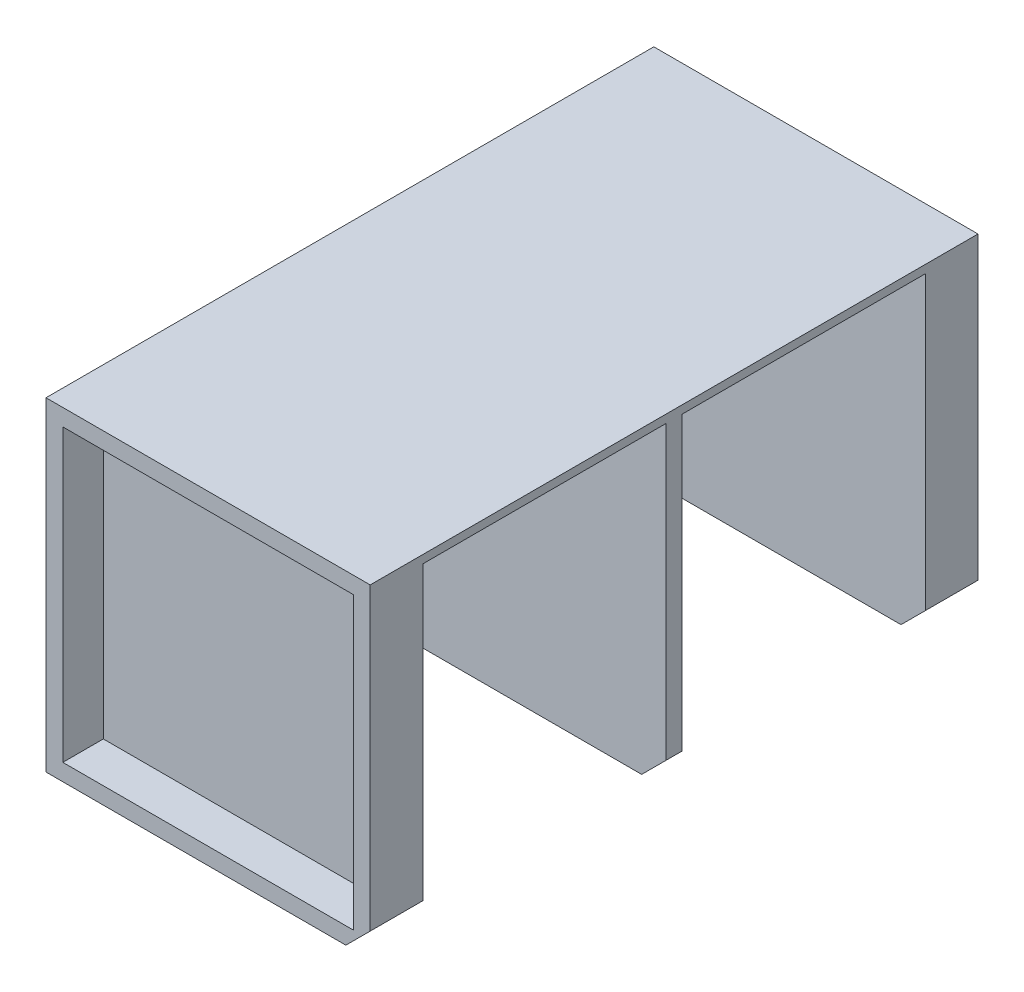
SolidWorks part; units mm, degrees
ref_plane "Front Plane" through (0, 0, 0) normal (1, 0, 0) x (0, 1, 0)
ref_plane "Top Plane" through (0, 0, 0) normal (0, 0, 1) x (0, 1, 0)
ref_plane "Right Plane" through (0, 0, 0) normal (0, 1, 0) x (-1, 0, 0)
sketch "Sketch1" plane through (0, 0, 0) normal (0, 0, 1) x (0, 1, 0)
  line L1 (-40, -40) -> (40, -40)
  line L2 (-40, -40) -> (-40, 40)
  line L3 (-40, 40) -> (40, 40)
  line L4 (40, -40) -> (40, 40)
  line L5 (-40, -40) -> (40, 40) construction
  line L6 (-40, 40) -> (40, -40) construction
  point P0 (0, 0)
  dimension "D1" = 80
  dimension "D2" = 80
extrude "Boss-Extrude1" add sketch "Sketch1" along normal blind 150
sketch "Sketch2" plane through (0, 0, 150) normal (0, 0, 1) x (1, 0, 0)
  line L1 (-35.85, -35.85) -> (35.85, -35.85)
  line L2 (-35.85, -35.85) -> (-35.85, 35.85)
  line L3 (-35.85, 35.85) -> (35.85, 35.85)
  line L4 (35.85, -35.85) -> (35.85, 35.85)
  line L5 (-35.85, -35.85) -> (35.85, 35.85) construction
  line L6 (-35.85, 35.85) -> (35.85, -35.85) construction
  point P0 (0, 0)
  dimension "D1" = 71.7
  dimension "D2" = 71.7
extrude "Cut-Extrude1-71.7square" cut sketch "Sketch2" against normal blind 10
ref_plane "Plane1-3mm-down-penholder-bottom" through (0, 0, 137) normal (0, 0, 1) x (1, 0, 0)
sketch "Sketch4" plane through (0, 0, 137) normal (0, 0, 1) x (1, 0, 0)
  line L1 (40, -40) -> (-38, -40)
  line L2 (40, -40) -> (40, 38)
  line L3 (40, 38) -> (-38, 38)
  line L4 (-38, -40) -> (-38, 38)
  dimension "D1" = 78
  dimension "D2" = 78
extrude "Cut-Extrude2-compartment1-6cm" cut sketch "Sketch4" against normal blind 60
ref_plane "Plane2-4mm-down-compartment1" through (0, 0, 73) normal (0, 0, 1) x (1, 0, 0)
sketch "Sketch5" plane through (0, 0, 73) normal (0, 0, 1) x (1, 0, 0)
  line L1 (40, -40) -> (-38, -40)
  line L2 (40, -40) -> (40, 38)
  line L3 (40, 38) -> (-38, 38)
  line L4 (-38, -40) -> (-38, 38)
  dimension "D1" = 78
  dimension "D2" = 78
extrude "Cut-Extrude3" cut sketch "Sketch5" against normal blind 60
ref_plane "Plane3-3mm-down-compartment2" through (0, 0, 10) normal (0, 0, 1) x (1, 0, 0)
sketch "Sketch6" plane through (0, 0, 10) normal (0, 0, -1) x (1, 0, 0)
  line L1 (-35.5, -35.5) -> (35.5, -35.5)
  line L2 (-35.5, -35.5) -> (-35.5, 35.5)
  line L3 (-35.5, 35.5) -> (35.5, 35.5)
  line L4 (35.5, -35.5) -> (35.5, 35.5)
  line L5 (-35.5, -35.5) -> (35.5, 35.5) construction
  line L6 (-35.5, 35.5) -> (35.5, -35.5) construction
  point P0 (0, 0)
  dimension "D1" = 71
extrude "Cut-Extrude4" cut sketch "Sketch6" along normal blind 60 draft 2
chamfer "Chamfer1" distance 6 angle 45 3 edges at (40, -40, 143.5) (40, -40, 75) (40, -40, 6.5)
